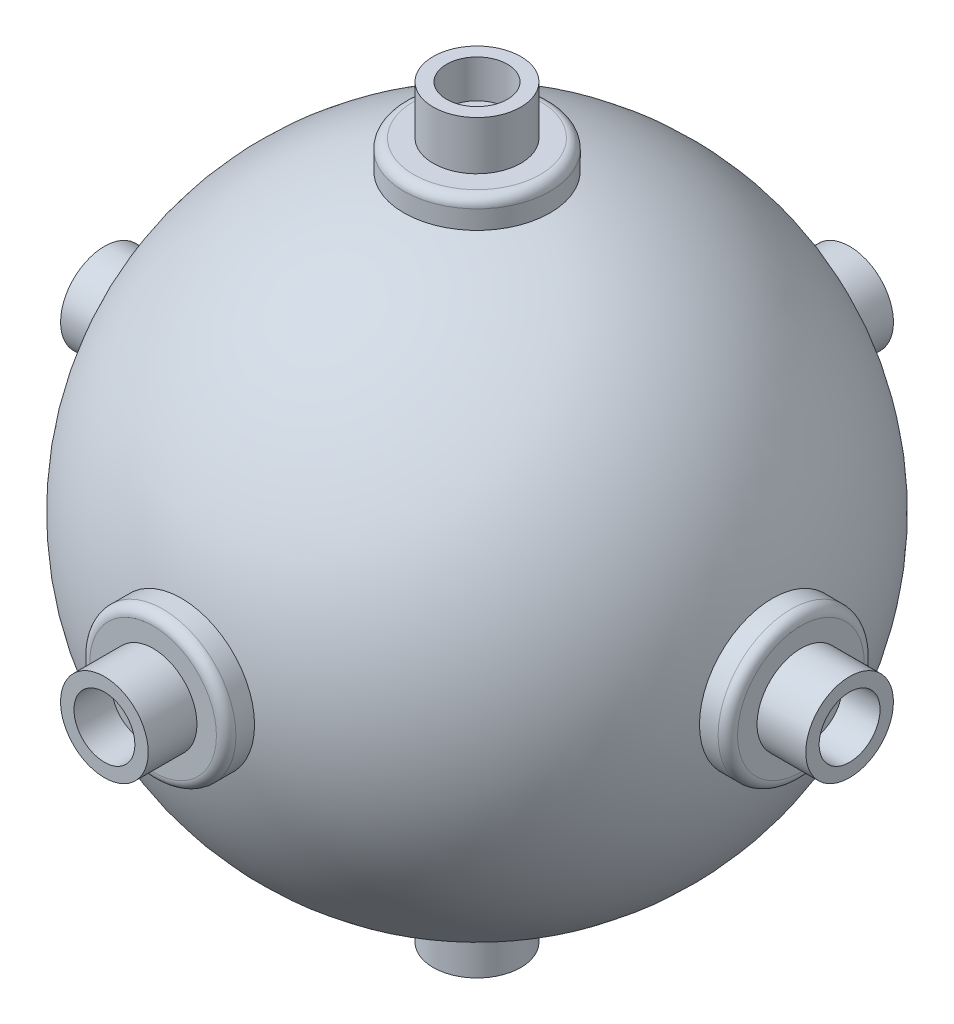
SolidWorks part; units mm, degrees
ref_plane "Front Plane" through (0, 0, 0) normal (0, 0, 1) x (1, 0, 0)
ref_plane "Top Plane" through (0, 0, 0) normal (0, 1, 0) x (1, 0, 0)
ref_plane "Right Plane" through (0, 0, 0) normal (1, 0, 0) x (0, 0, -1)
sketch "Sketch1" plane through (0, 0, 0) normal (0, 0, 1) x (1, 0, 0)
  line L0 (0, 15.875) -> (0, -15.875)
  arc A0 (0, 15.875) -> (0, -15.875) centre (0, 0) ccw
revolve "Revolve1" add sketch "Sketch1" angle 360 about L0
sketch "Sketch2" plane through (0, 0, 0) normal (0, 0, 1) x (1, 0, 0)
  circle A0 centre (0, 0) radius 15.875 construction
  point P0 (0, 15.875)
  point P1 (0, -15.875)
  point P4 (15.875, 0)
  point P5 (-15.875, 0)
sketch "Sketch5" plane through (0, 0, 0) normal (1, 0, 0) x (0, 0, -1)
  circle A0 centre (0, 0) radius 15.875 construction
  point P0 (-15.875, 0)
  point P1 (15.875, 0)
ref_plane "Plane2" through (0, 0, 15.875) normal (0, 0, 1) x (1, 0, 0)
sketch "Sketch6" plane through (0, 0, 15.875) normal (0, 0, 1) x (1, 0, 0)
  circle A0 centre (0, 0) radius 3.81
extrude "Boss-Extrude1" add sketch "Sketch6" along normal mid plane 2.032 contours A0
sketch "Sketch7" plane through (0, 0, 0) normal (0, 0, 1) x (1, 0, 0)
  line L0 (0, 15.875) -> (0, -15.875) construction
sketch "Sketch9" plane through (0, 0, 16.891) normal (0, 0, 1) x (1, 0, 0)
  circle A0 centre (0, 0) radius 2.286
extrude "Boss-Extrude3" add sketch "Sketch9" along normal blind 2.54
pattern_circular "CirPattern1" count 4 over 360 about axis through (0, 0, 0) along (0, 1, 0) of "Boss-Extrude1", "Boss-Extrude3"
ref_plane "Plane3" through (0, 15.875, 0) normal (0, 1, 0) x (1, 0, 0)
sketch "Sketch10" plane through (0, 15.875, 0) normal (0, 1, 0) x (1, 0, 0)
  circle A0 centre (0, 0) radius 3.81
extrude "Boss-Extrude4" add sketch "Sketch10" along normal mid plane 2.032
sketch "Sketch11" plane through (0, 16.891, 0) normal (0, 1, 0) x (1, 0, 0)
  circle A0 centre (0, 0) radius 2.286
extrude "Boss-Extrude5" add sketch "Sketch11" along normal blind 2.54
mirror "Mirror1" about plane through (0, 0, 0) normal (0, 1, 0) of "Boss-Extrude4", "Boss-Extrude5"
hole_wizard "CBORE for #00 Binding Head Machine Screw1" positions "Sketch12" profile "Sketch13" counterbore size "#00" standard "ANSI Inch"
sketch "Sketch12" plane through (0, 19.431, 0) normal (0, 1, 0) x (1, 0, 0)
  point P0 (0, 0)
sketch "Sketch13" plane through (0, 19.431, 0) normal (1, 0, 0) x (0, 0, 1)
  line L0 (0, 0) -> (0, 4.2297)
  line L1 (0, 4.2297) -> (0.6985, 3.81)
  line L2 (0.6985, 3.81) -> (0.6985, 1.9812)
  line L3 (0.6985, 1.9812) -> (1.5875, 1.9812)
  line L4 (1.5875, 1.9812) -> (1.5875, 0)
  line L5 (1.5875, 0) -> (0, 0)
  line L10 (0, 4.2297) -> (-0.6985, 3.81) construction
  line L11 (0, -6.35) -> (0, 107.95) construction
  dimension "Hole Dia." = 1.397
  dimension "Hole Depth" = 3.81
  dimension "C'Bore Dia." = 3.175
  dimension "C'Bore Depth" = 1.9812
  dimension "Drill Angle" = 118
sketch "Sketch15" plane through (0, 0, 0) normal (0, 1, 0) x (1, 0, 0)
  line L0 (-15.875, 0) -> (15.875, 0) construction
pattern_circular "CirPattern2" count 4 every 90 about axis through (0, 0, 0) along (1, 0, 0) of "CBORE for #00 Binding Head Machine Screw1"
hole_wizard "CBORE for #00 Binding Head Machine Screw3" positions "Sketch18" profile "Sketch19" counterbore size "#00" standard "ANSI Inch"
sketch "Sketch18" plane through (19.431, 0, 0) normal (1, 0, 0) x (0, 0, -1)
  point P0 (0, 0)
sketch "Sketch19" plane through (19.431, 0, 0) normal (0, 1, 0) x (0, 0, -1)
  line L0 (0, 0) -> (0, 4.2297)
  line L1 (0, 4.2297) -> (0.6985, 3.81)
  line L2 (0.6985, 3.81) -> (0.6985, 1.9812)
  line L3 (0.6985, 1.9812) -> (1.5875, 1.9812)
  line L4 (1.5875, 1.9812) -> (1.5875, 0)
  line L5 (1.5875, 0) -> (0, 0)
  line L10 (0, 4.2297) -> (-0.6985, 3.81) construction
  line L11 (0, -6.35) -> (0, 107.95) construction
  dimension "Hole Dia." = 1.397
  dimension "Hole Depth" = 3.81
  dimension "C'Bore Dia." = 3.175
  dimension "C'Bore Depth" = 1.9812
  dimension "Drill Angle" = 118
mirror "Mirror2" about plane through (0, 0, 0) normal (1, 0, 0) of "CBORE for #00 Binding Head Machine Screw3"
fillet "Fillet1" radius 0.508 6 edges at (-3.81, 0, -16.891) (0, -16.891, 3.81) (-16.891, 0, 3.81) (16.891, 0, -3.81) (3.81, 0, 16.891) (0, 16.891, 3.81)
